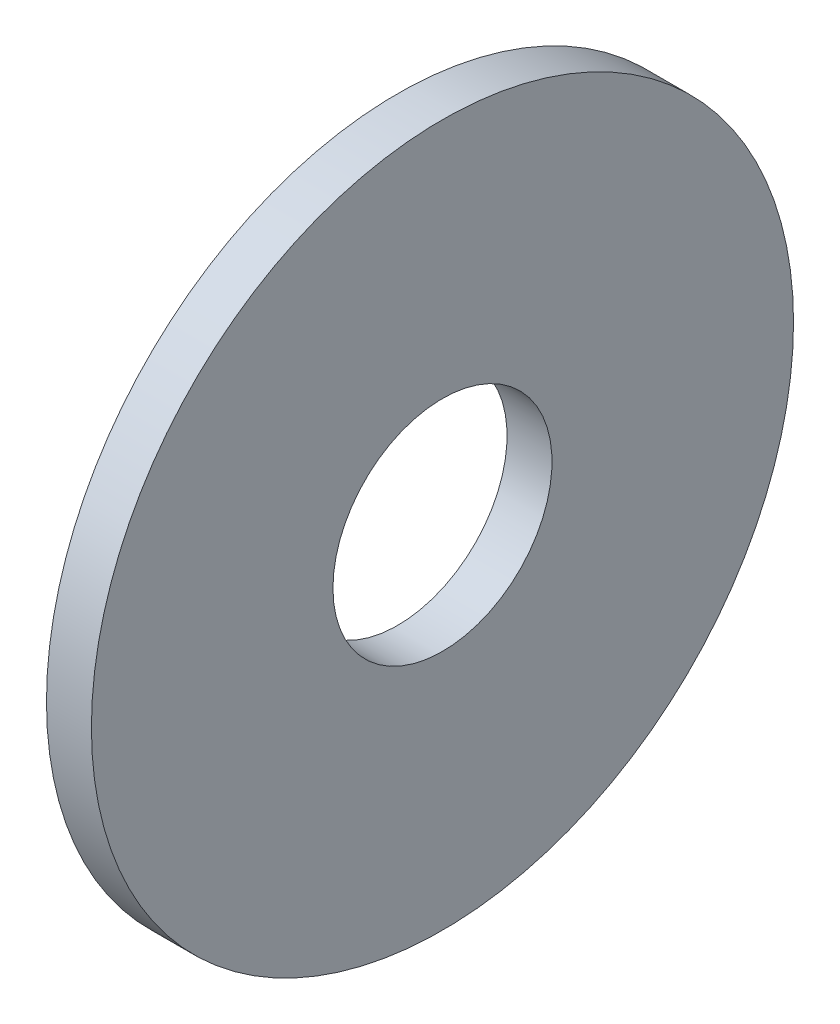
SolidWorks part; units mm, degrees
ref_plane "Plane1" through (0, 0, 0) normal (0, 0, 1) x (1, 0, 0)
ref_plane "Plane2" through (0, 0, 0) normal (0, 1, 0) x (1, 0, 0)
ref_plane "Plane3" through (0, 0, 0) normal (1, 0, 0) x (0, 0, -1)
sketch "Sketch1" plane through (0, 0, 0) normal (0, 0, 1) x (1, 0, 0)
  line L0 (-34.925, 0) -> (9.525, 0) construction
  line L1 (0, 19.5) -> (0, 62.5)
  line L2 (0, 62.5) -> (-8, 62.5)
  line L3 (-8, 62.5) -> (-8, 19.5)
  line L4 (-8, 19.5) -> (0, 19.5)
  dimension "Thickness" = 8
  dimension "Inside_dia" = 39
  dimension "Outside_dia" = 125
revolve "Base-Revolve" add sketch "Sketch1" angle 360 about L0
